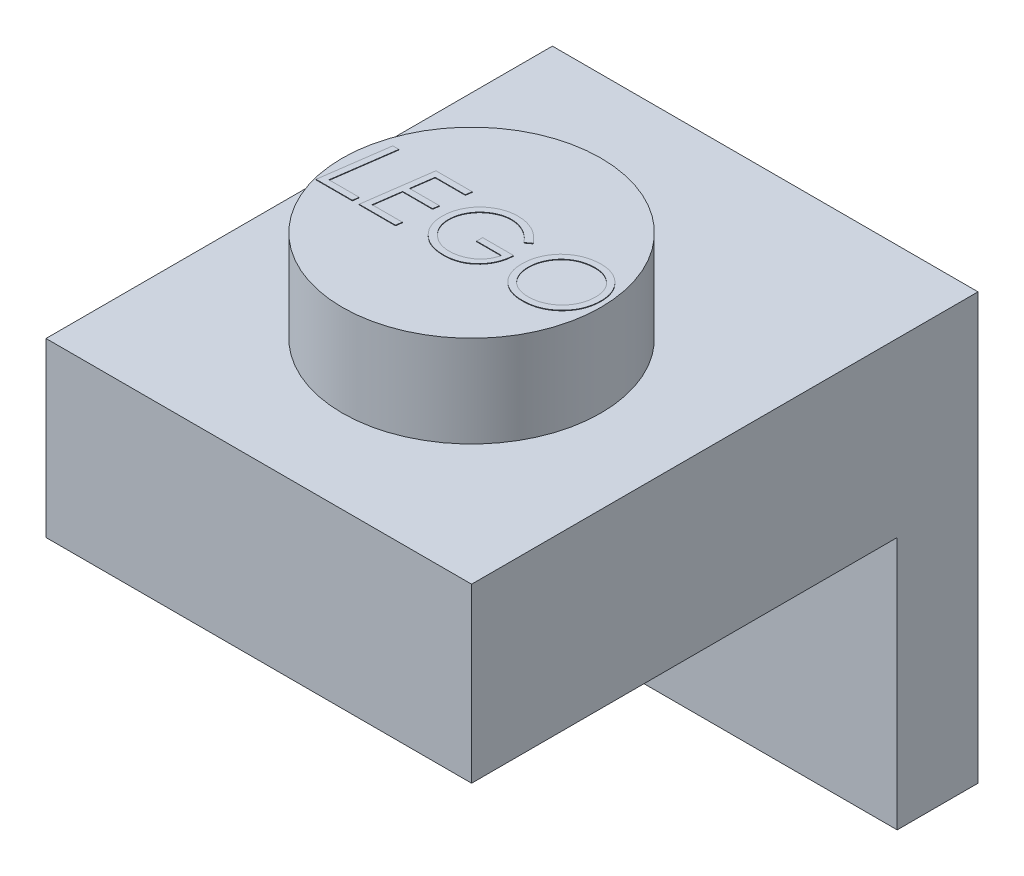
SolidWorks part; units mm, degrees
ref_plane "Front Plane" through (0, 0, 0) normal (0, 0, 1) x (1, 0, 0)
ref_plane "Top Plane" through (0, 0, 0) normal (0, 1, 0) x (1, 0, 0)
ref_plane "Right Plane" through (0, 0, 0) normal (1, 0, 0) x (0, 0, -1)
sketch "Sketch1" plane through (0, 0, 0) normal (0, 1, 0) x (1, 0, 0)
  line L0 (0, 0) -> (7.9, 0)
  line L1 (7.9, 0) -> (7.9, 7.9)
  line L2 (0, 0) -> (0, 7.9)
  line L3 (0, 7.9) -> (7.9, 7.9)
  dimension "D1" = 7.9
  dimension "D2" = 7.9
  dimension "D3" = 7.9
extrude "Boss-Extrude1" add sketch "Sketch1" along normal blind 3.2
sketch "Sketch2" plane through (0, 3.2, 0) normal (0, 1, 0) x (1, 0, 0)
  line L0 (0, 7.9) -> (7.9, 0) construction
  circle A0 centre (3.95, 3.95) radius 2.4
extrude "Boss-Extrude2" add sketch "Sketch2" along normal blind 1.7
sketch "Sketch3" plane through (0, 4.9, 0) normal (0, 1, 0) x (1, 0, 0)
  line L0 (1.625, 3.3549) -> (6.275, 3.3549) construction
  circle A0 centre (3.95, 3.95) radius 2.4 construction
  circle A1 centre (3.95, 3.95) radius 2.4 construction
  text T0 "<i>LEGO</i>" font "Century Gothic" height 1.25
extrude "Boss-Extrude4" add sketch "Sketch3" along normal blind 0.01
sketch "Sketch4" plane through (0, 0, 0) normal (0, -1, 0) x (1, 0, 0)
  line L0 (7.9, -7.9) -> (0, -7.9) construction
  line L1 (7.3, -7.3) -> (0.6204, -7.3)
  line L2 (7.3, -7.3) -> (7.3, -0.6204)
  line L3 (7.3, -0.6204) -> (0.6204, -0.6204)
  line L4 (0.6204, -7.3) -> (0.6204, -0.6204)
  line L5 (7.9, 0) -> (7.9, -7.9) construction
  dimension "D1" = 0.6
  dimension "D2" = 0.6
extrude "Cut-Extrude1" cut sketch "Sketch4" against normal blind 2.01 contours L2 L1 L4 L3
sketch "Sketch5" plane through (0, 3.2, 0) normal (0, 1, 0) x (1, 0, 0)
  line L1 (1.4581, 1.5578) -> (6.3695, 1.5578)
  line L2 (1.4581, 1.5578) -> (1.4581, 6.3652)
  line L3 (1.4581, 6.3652) -> (6.3695, 6.3652)
  line L4 (6.3695, 1.5578) -> (6.3695, 6.3652)
  circle A1 centre (6.3695, 6.3652) radius 1.0161
  circle A2 centre (6.3695, 1.5578) radius 1.0061
  circle A3 centre (1.4581, 1.5578) radius 1.0219
  circle A4 centre (1.4581, 6.3652) radius 1.0411
  circle M5 centre (3.95, 3.95) radius 2.4
extrude "Boss-Extrude5" add sketch "Sketch5" against normal blind 2.01 contours L1 A2 L4 | L2 A3 L1 | L1 A3 L2 | L4 A2 L1 M5 | L4 A1 L3 | L3 A1 L4 | L2 A4 L3 | L3 A4 L2
sketch "Sketch6" plane through (0, 0, -7.9) normal (0, 0, -1) x (-1, 0, 0)
  line L1 (-7.9, 3.2) -> (0, 3.2)
  line L2 (-7.9, 3.2) -> (-7.9, -4.7)
  line L3 (-7.9, -4.7) -> (0, -4.7)
  line L4 (0, 3.2) -> (0, -4.7)
  dimension "D1" = 7.9
extrude "Boss-Extrude6" add sketch "Sketch6" along normal blind 1.5 contours L2 L3 L4 L1
sketch "Sketch7" plane through (0, 0, -9.4) normal (0, 0, -1) x (-1, 0, 0)
  line L0 (-7.9, 3.2) -> (0, -4.7) construction
  circle A0 centre (-3.95, -0.75) radius 2.4
  dimension "D1" = 4.8
extrude "Boss-Extrude7" add sketch "Sketch7" along normal blind 1.4
sketch "Sketch8" plane through (0, 0, -10.8) normal (0, 0, -1) x (-1, 0, 0)
  line L0 (-3.95, 1.65) -> (-3.95, -3.15) construction
  circle A0 centre (-3.95, -0.75) radius 2.4 construction
  circle A1 centre (-3.95, -0.75) radius 2.4 construction
  circle A2 centre (-3.95, -0.75) radius 1.6901
extrude "Cut-Extrude2" cut sketch "Sketch8" against normal up to surface (1.4 mm away) up to face at (1.55, -0.75, -9.4)
